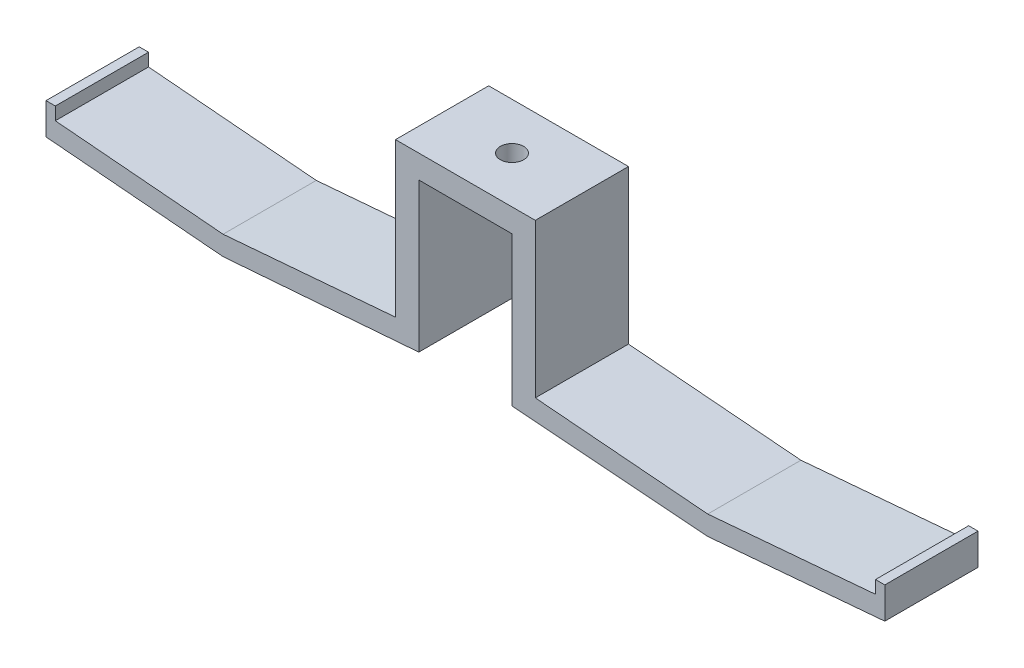
SolidWorks part; units mm, degrees
material "1345 Alloy"
ref_plane "Front Plane" through (0, 0, 0) normal (0, 0, 1) x (1, 0, 0)
ref_plane "Top Plane" through (0, 0, 0) normal (0, 1, 0) x (1, 0, 0)
ref_plane "Right Plane" through (0, 0, 0) normal (1, 0, 0) x (0, 0, -1)
sketch "Sketch2" plane through (0, 0, 0) normal (0, 0, 1) x (1, 0, 0)
  line L1 (12.7, 0) -> (12.7, -40.64)
  line L2 (12.7, -40.64) -> (66.04, -44.7734)
  line L3 (66.04, -44.7734) -> (114.3, -40.64)
  line L4 (114.3, -40.64) -> (114.3, -32.0734)
  line L5 (111.76, -32.0734) -> (111.76, -35.56)
  line L6 (111.76, -35.56) -> (66.04, -39.4758)
  line L19 (114.3, -32.0734) -> (111.76, -32.0734)
  line L20 (0, 125.2351) -> (0, -75.9356) construction
  line L21 (12.7, 0) -> (-12.7, 0)
  line L22 (0, 0) -> (0, 6.35)
  line L23 (19.05, 6.35) -> (-19.05, 6.35)
  line L24 (19.05, 6.35) -> (19.05, 0)
  line L25 (19.05, 0) -> (19.05, -35.56)
  line L26 (19.05, -35.56) -> (66.04, -39.4758)
  line L27 (-19.05, 0) -> (-19.05, -35.56)
  line L28 (-19.05, 6.35) -> (-19.05, 0)
  line L29 (-12.7, 0) -> (-12.7, -40.64)
  line L30 (-12.7, -40.64) -> (-66.04, -44.7734)
  line L31 (-66.04, -44.7734) -> (-114.3, -40.64)
  line L32 (-114.3, -40.64) -> (-114.3, -32.0734)
  line L33 (-114.3, -32.0734) -> (-111.76, -32.0734)
  line L34 (-111.76, -32.0734) -> (-111.76, -35.56)
  line L35 (-111.76, -35.56) -> (-66.04, -39.4758)
  line L36 (-19.05, -35.56) -> (-66.04, -39.4758)
  dimension "D1" = 19.05
  dimension "D2" = 12.7
  dimension "D3" = 35.56
  dimension "D4" = 3.9158
  dimension "D5" = 40.64
  dimension "D6" = 2.54
  dimension "D7" = 45.72
  dimension "D8" = 46.99
  dimension "D9" = 12.7
  dimension "D10" = 6.35
extrude "Boss-Extrude1" add sketch "Sketch2" along normal blind 25.4 contours L26 L25 L24 L23 L22 L21 L1 L2 L3 L4 L19 L5 L6 | L27 L36 L35 L34 L33 L32 L31 L30 L29 L21 L22 L23 L28
sketch "Sketch3" plane through (0, 6.35, 0) normal (0, 1, 0) x (1, 0, 0)
  line L0 (19.05, -12.7) -> (-19.05, -12.7) construction
  line L1 (19.05, -25.4) -> (19.05, 0) construction
  line L2 (-19.05, -25.4) -> (-19.05, 0) construction
  circle A0 centre (0, -12.7) radius 3.175
  dimension "D1" = 6.35
extrude "Cut-Extrude1" cut sketch "Sketch3" against normal up to next
